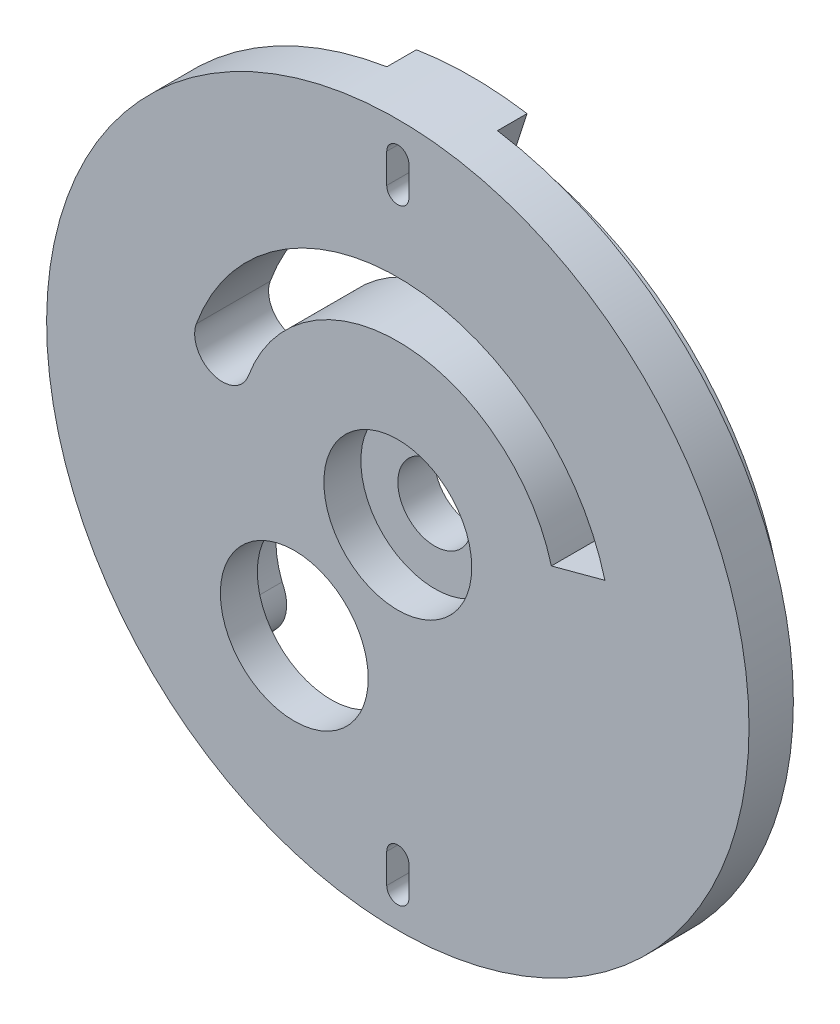
SolidWorks part; units mm, degrees
ref_plane "Plan de face" through (0, 0, 0) normal (0, 0, 1) x (1, 0, 0)
ref_plane "Plan de dessus" through (0, 0, 0) normal (0, 1, 0) x (1, 0, 0)
ref_plane "Plan de droite" through (0, 0, 0) normal (1, 0, 0) x (0, 0, -1)
sketch "Esquisse1" plane through (0, 0, 0) normal (0, 0, 1) x (1, 0, 0)
  line L0 (0, -780) -> (0, -860) construction
  line L1 (30, -780) -> (30, -860)
  line L2 (-30, -780) -> (-30, -860)
  line L3 (-404.0678, 147.0687) -> (-545.0217, 198.3717) construction
  line L4 (415.3481, 111.2922) -> (560.237, 150.115)
  line L5 (0, -1117.3618) -> (0, 1072.3515) construction
  line L6 (1131.676, 0) -> (-1325.7304, 0) construction
  line L7 (0, 780) -> (0, 860) construction
  line L8 (30, 780) -> (30, 860)
  line L9 (-30, 780) -> (-30, 860)
  circle A0 centre (0, 0) radius 950
  circle A1 centre (0, 0) radius 100
  circle A2 centre (-280, -400) radius 200
  arc A3 (-545.0217, 198.3717) -> (560.237, 150.115) centre (0, 0) cw
  arc A4 (415.3481, 111.2922) -> (-404.0678, 147.0687) centre (0, 0) ccw
  arc A5 (30, -780) -> (-30, -780) centre (0, -780) ccw
  arc A6 (-30, -860) -> (30, -860) centre (0, -860) ccw
  arc A7 (-545.0217, 198.3717) -> (-404.0678, 147.0687) centre (-474.5448, 172.7202) ccw
  arc A8 (30, 780) -> (-30, 780) centre (0, 780) cw
  arc A9 (-30, 860) -> (30, 860) centre (0, 860) cw
  circle A10 centre (0, 0) radius 200
  point P10 (0, -820)
  point P17 (-474.5448, 172.7202)
  point P30 (0, 820)
  dimension "D1" = 1900
  dimension "D2" = 200
  dimension "D3" = 400
  dimension "D8" = 30
  dimension "D9" = 430
  dimension "D10" = 580
  dimension "D13" = 400
  dimension "D4" = 400
  dimension "D5" = 280
  dimension "D6" = 80
  dimension "D7" = 780
  dimension "D11" = 70
  dimension "D12" = 15
extrude "Boss.-Extru.2" add sketch "Esquisse1" along normal blind 200 contours A0 A10 A7 A3 L4 A4 A6 L2 A5 L1 A2 L9 A9 L8 A8 | A1
sketch "Esquisse4" plane through (0, 0, 200) normal (0, 0, 1) x (1, 0, 0)
  circle A0 centre (0, 0) radius 200
  dimension "D1" = 400
extrude "Enlèv. mat.-Extru.2" cut sketch "Esquisse4" against normal blind 100
sketch "Esquisse5" plane through (0, 0, 0) normal (0, 0, -1) x (-1, 0, 0)
  line L0 (-118.2971, 841.7279) -> (-149.6244, 938.1431)
  line L1 (-118.2971, -841.7279) -> (-149.6244, -938.1431)
  line L2 (0, 1088.8741) -> (0, -1219.7765) construction
  line L3 (-118.2971, -841.7279) -> (0, 0) construction
  line L4 (0, 0) -> (-118.2971, 841.7279) construction
  line L5 (118.2971, 841.7279) -> (149.6244, 938.1431)
  line L6 (118.2971, -841.7279) -> (149.6244, -938.1431)
  line L7 (-532.6162, -93.9146) -> (-432.0826, -76.1878)
  line L8 (84.9986, -706.147) -> (148.7618, -836.8811)
  line L9 (525.2369, -604.2159) -> (557.6502, -641.5031)
  line L10 (1183.662, 0) -> (-1419.1951, 0) construction
  arc A0 (-118.2971, 841.7279) -> (-118.2971, -841.7279) centre (0, 0) ccw
  circle A1 centre (0, 0) radius 950 construction
  arc A2 (-149.6244, 938.1431) -> (-149.6244, -938.1431) centre (0, 0) ccw
  arc A3 (118.2971, 841.7279) -> (118.2971, -841.7279) centre (0, 0) cw
  arc A4 (149.6244, 938.1431) -> (149.6244, -938.1431) centre (0, 0) cw
  arc A5 (513.0523, -490.4799) -> (55.5989, -289.7996) centre (280, -400) ccw
  arc A6 (-49.042, -346.5471) -> (-322.5583, -135.8534) centre (0, 0) cw
  arc A7 (-4.2301, -649.9862) -> (-608.9335, -227.3764) centre (0, 0) cw
  arc A8 (557.6502, -641.5031) -> (201.8633, -825.6823) centre (0, 0) cw
  arc A9 (-608.9335, -227.3764) -> (-532.6162, -93.9146) centre (-515.2514, -192.3954) cw
  arc A10 (-322.5583, -135.8534) -> (-432.0826, -76.1878) centre (-414.7178, -174.6686) ccw
  arc A11 (513.0523, -490.4799) -> (525.2369, -604.2159) centre (600.7078, -538.61) ccw
  arc A12 (-4.2301, -649.9862) -> (84.9986, -706.147) centre (-4.8808, -749.9841) cw
  arc A13 (55.5989, -289.7996) -> (-49.042, -346.5471) centre (-35.03, -247.5336) cw
  point P17 (0, 0)
  point P36 (0, 0)
  point P37 (63.8058, -293.8299)
  point P39 (0, 0)
  point P40 (0, 0)
  point P41 (0, 0)
  circle M20 centre (280, -400) radius 200
  dimension "D1" = 170
  dimension "D3" = 100
  dimension "D6" = 350
  dimension "D7" = 100
  dimension "D8" = 650
  dimension "D9" = 10
  dimension "D13" = 250
  dimension "D14" = 224.4011
  dimension "D2" = 8
  dimension "D4" = 8
  dimension "D5" = 170
  dimension "D10" = 15
  dimension "D11" = 8
  dimension "D12" = 63.7633
  dimension "D15" = 320.7078
extrude "Enlèv. mat.-Extru.3" cut sketch "Esquisse5" against normal blind 100 contours A5 A13 A6 A10 L7 A9 A7 A12 L8 A3 L9 A11 M20
sketch "Esquisse6" plane through (0, 0, 0) normal (0, 0, -1) x (-1, 0, 0)
  line L0 (-118.2971, 841.7279) -> (-149.6244, 938.1431)
  line L1 (-118.2971, -841.7279) -> (-149.6244, -938.1431)
  line L2 (0, 0) -> (-118.2971, 841.7279) construction
  line L3 (0, 0) -> (-118.2971, -841.7279) construction
  line L4 (0, -1051.5573) -> (0, 1037.6067) construction
  line L5 (118.2971, 841.7279) -> (149.6244, 938.1431)
  line L6 (118.2971, -841.7279) -> (149.6244, -938.1431)
  line L7 (0, 0) -> (118.2971, -841.7279) construction
  arc A0 (-118.2971, 841.7279) -> (-118.2971, -841.7279) centre (0, 0) ccw
  circle A1 centre (0, 0) radius 950 construction
  arc A2 (-149.6244, 938.1431) -> (-149.6244, -938.1431) centre (0, 0) ccw
  arc A3 (118.2971, 841.7279) -> (118.2971, -841.7279) centre (0, 0) cw
  arc A4 (149.6244, 938.1431) -> (149.6244, -938.1431) centre (0, 0) cw
  point P12 (0, 0)
  dimension "D1" = 100
  dimension "D2" = 8
  dimension "D3" = 170
  dimension "D4" = 8
  dimension "D5" = 170
extrude "Enlèv. mat.-Extru.4" cut sketch "Esquisse6" against normal blind 80 contours L1 A2 L0 A0 | A3 L6 A4 L5
